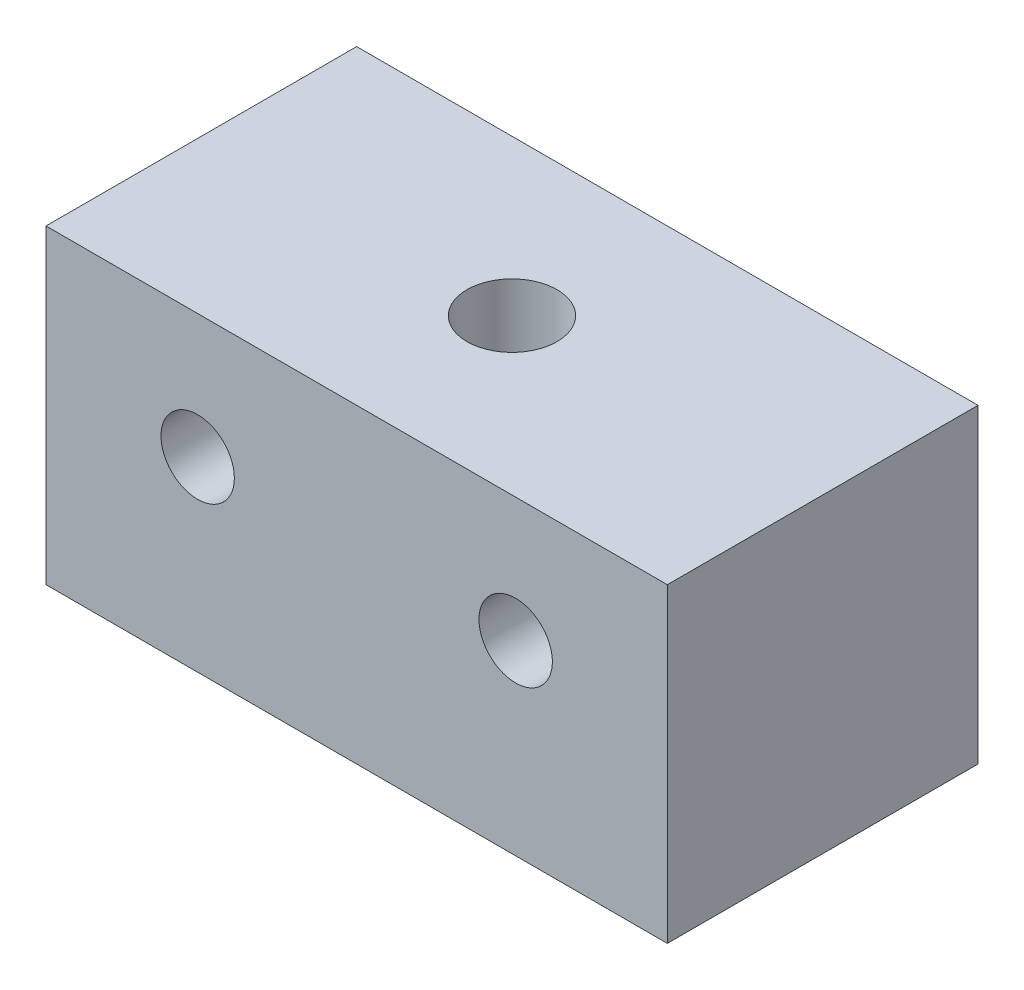
SolidWorks part; units mm, degrees
ref_plane "Front" through (0, 0, 0) normal (0, 0, 1) x (1, 0, 0)
ref_plane "Top" through (0, 0, 0) normal (0, 1, 0) x (1, 0, 0)
ref_plane "Right" through (0, 0, 0) normal (1, 0, 0) x (0, 0, -1)
sketch "Sketch1" plane through (0, 0, 0) normal (0, 1, 0) x (1, 0, 0)
  line L1 (0, 0) -> (25.4, 0)
  line L2 (0, 0) -> (0, 12.7)
  line L3 (0, 12.7) -> (25.4, 12.7)
  line L4 (25.4, 0) -> (25.4, 12.7)
  dimension "D1" = 12.7
  dimension "D2" = 25.4
extrude "Boss-Extrude1" add sketch "Sketch1" along normal blind 12.7
sketch "Sketch2" plane through (0, 0, 0) normal (0, 0, 1) x (1, 0, 0)
  line L0 (12.7, 12.7) -> (12.7, 0) construction
  line L1 (0, 12.7) -> (25.4, 12.7) construction
  line L2 (0, 0) -> (25.4, 0) construction
  circle A0 centre (6.2, 7.62) radius 1.5
  circle A1 centre (19.2, 7.62) radius 1.5
  dimension "D1" = 3
  dimension "D2" = 6.5
  dimension "D3" = 5.08
extrude "Cut-Extrude1" cut sketch "Sketch2" against normal through all
sketch "Sketch3" plane through (0, 12.7, 0) normal (0, 1, 0) x (1, 0, 0)
  line L0 (12.7, 0) -> (12.7, 12.7) construction
  line L1 (0, 0) -> (25.4, 0) construction
  line L2 (25.4, 12.7) -> (0, 12.7) construction
  line L3 (12.7, 12.7) -> (25.4, 6.35) construction
  line L4 (25.4, 0) -> (25.4, 12.7) construction
  line L5 (25.4, 6.35) -> (0, 6.35) construction
  line L6 (0, 12.7) -> (0, 0) construction
  circle A0 centre (12.7, 6.35) radius 1.8415
  dimension "D1" = 3.683
extrude "Cut-Extrude2" cut sketch "Sketch3" against normal through all
